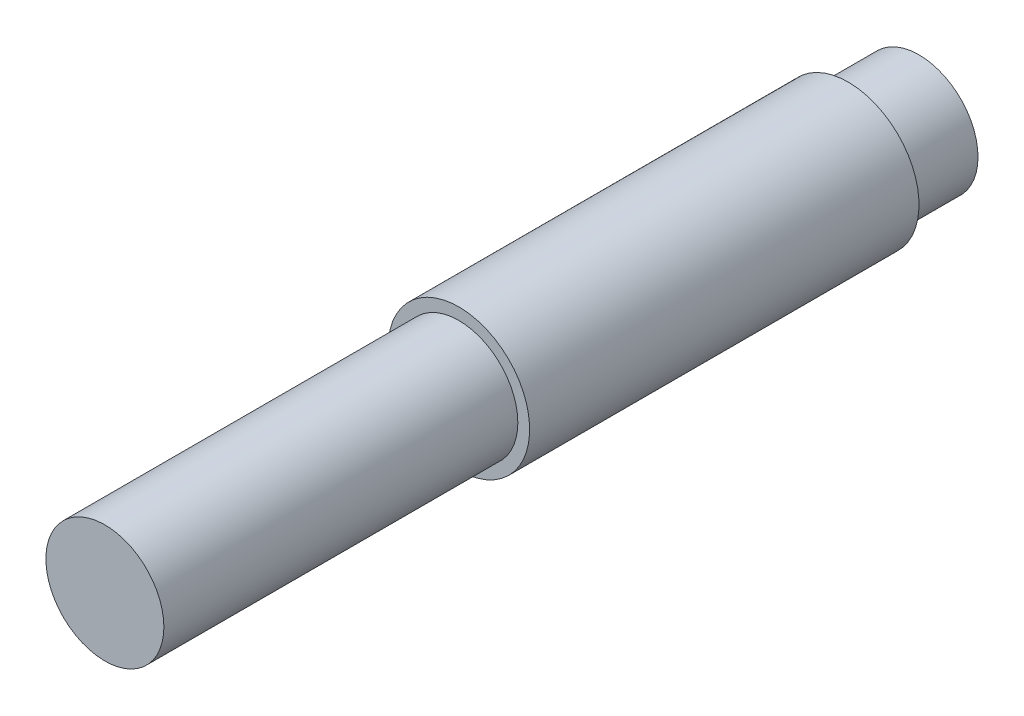
SolidWorks part; units mm, degrees
ref_plane "Front" through (0, 0, 0) normal (0, 0, 1) x (1, 0, 0)
ref_plane "Top" through (0, 0, 0) normal (0, 1, 0) x (1, 0, 0)
ref_plane "Right" through (0, 0, 0) normal (1, 0, 0) x (0, 0, -1)
sketch "Эскиз1" plane through (0, 0, 0) normal (0, 0, 1) x (1, 0, 0)
  circle A0 centre (0.2803, 0.0027) radius 1.4106
  circle A1 centre (0.2803, 0.0027) radius 2.5
  dimension "D1" = 5
extrude "Бобышка-Вытянуть1" add sketch "Эскиз1" against normal blind 3
sketch "Эскиз2" plane through (0, 0, 0) normal (0, 0, 1) x (1, 0, 0)
  circle A0 centre (0.2803, 0.0027) radius 3
  dimension "D1" = 6
extrude "Бобышка-Вытянуть2" add sketch "Эскиз2" along normal up to surface (16.5 mm away)
sketch "Эскиз3" plane through (0, 0, 16.5) normal (0, 0, 1) x (1, 0, 0)
  circle A0 centre (0.2803, 0.0027) radius 2.5
  dimension "D1" = 5
extrude "Бобышка-Вытянуть3" add sketch "Эскиз3" along normal blind 15
